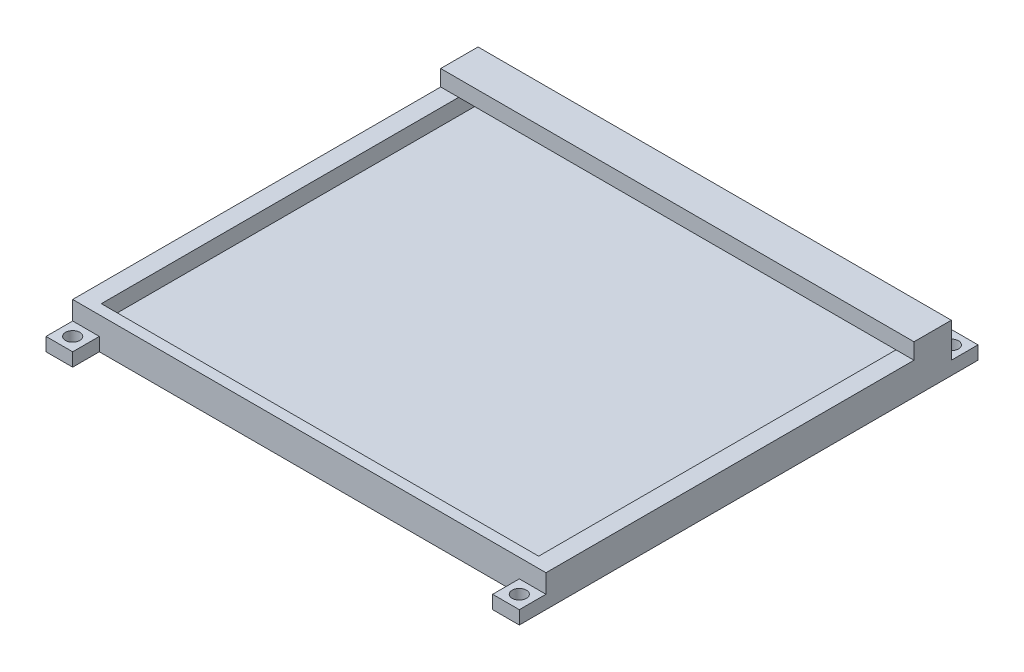
SolidWorks part; units mm, degrees
ref_plane "Front Plane" through (0, 0, 0) normal (0, 0, 1) x (1, 0, 0)
ref_plane "Top Plane" through (0, 0, 0) normal (0, 1, 0) x (1, 0, 0)
ref_plane "Right Plane" through (0, 0, 0) normal (1, 0, 0) x (0, 0, -1)
sketch "Sketch1" plane through (0, 0, 0) normal (0, 1, 0) x (1, 0, 0)
  line L1 (0, 0) -> (112.7, 0)
  line L2 (0, 0) -> (0, 96.52)
  line L3 (0, 96.52) -> (112.7, 96.52)
  line L4 (112.7, 0) -> (112.7, 96.52)
  dimension "D1" = 112.7
  dimension "D2" = 96.52
extrude "Boss-Extrude1" add sketch "Sketch1" along normal blind 7.62
sketch "Sketch2" plane through (0, 7.62, 0) normal (0, 1, 0) x (1, 0, 0)
  line L0 (0, 0) -> (112.7, 0) construction
  line L1 (4.28, 2.54) -> (108.42, 2.54)
  line L2 (4.28, 2.54) -> (4.28, 93.98)
  line L3 (4.28, 93.98) -> (108.42, 93.98)
  line L4 (108.42, 2.54) -> (108.42, 93.98)
  line L6 (0, 96.52) -> (0, 0) construction
  point P6 (56.35, 2.54)
  point P7 (56.35, 0)
  point P8 (4.28, 48.26)
  point P11 (0, 48.26)
  dimension "D1" = 104.14
  dimension "D2" = 91.44
  dimension "D3" = 0
  dimension "D4" = 0
extrude "Cut-Extrude1" cut sketch "Sketch2" against normal blind 3.81
sketch "Sketch3" plane through (0, 0, 0) normal (0, -1, 0) x (1, 0, 0)
  line L1 (112.7, 0) -> (106.35, 0)
  line L2 (112.7, 0) -> (112.7, 6.35)
  line L3 (112.7, 6.35) -> (106.35, 6.35)
  line L4 (106.35, 0) -> (106.35, 6.35)
  line L5 (0, 0) -> (6.35, 0)
  line L6 (0, 0) -> (0, 6.35)
  line L7 (0, 6.35) -> (6.35, 6.35)
  line L8 (6.35, 0) -> (6.35, 6.35)
  line L9 (0, -96.52) -> (6.35, -96.52)
  line L10 (0, -96.52) -> (0, -102.87)
  line L11 (0, -102.87) -> (6.35, -102.87)
  line L12 (6.35, -96.52) -> (6.35, -102.87)
  line L13 (112.7, -96.52) -> (106.35, -96.52)
  line L14 (112.7, -96.52) -> (112.7, -102.87)
  line L15 (112.7, -102.87) -> (106.35, -102.87)
  line L16 (106.35, -96.52) -> (106.35, -102.87)
  circle A0 centre (3.175, 3.175) radius 1.7
  circle A1 centre (109.525, 3.175) radius 1.7
  circle A2 centre (3.175, -99.695) radius 1.7
  circle A3 centre (109.525, -99.695) radius 1.7
  dimension "D9" = 3.4
  dimension "D10" = 3.4
  dimension "D11" = 3.4
  dimension "D12" = 3.4
  dimension "D1" = 6.35
  dimension "D2" = 6.35
  dimension "D3" = 6.35
  dimension "D4" = 6.35
  dimension "D5" = 6.35
  dimension "D6" = 6.35
  dimension "D7" = 6.35
  dimension "D8" = 6.35
extrude "Boss-Extrude2" add sketch "Sketch3" against normal blind 3.175
sketch "Sketch4" plane through (0, 7.62, 0) normal (0, 1, 0) x (1, 0, 0)
  line L0 (112.7, 0) -> (112.7, 96.52) construction
  line L1 (0, 96.52) -> (112.7, 96.52)
  line L2 (0, 96.52) -> (0, 87.63)
  line L3 (0, 87.63) -> (112.7, 87.63)
  line L4 (112.7, 96.52) -> (112.7, 87.63)
  line L6 (108.42, 93.98) -> (4.28, 93.98) construction
  dimension "D1" = 8.89
  dimension "D2" = 2.54
extrude "Boss-Extrude3" add sketch "Sketch4" along normal blind 3.81
